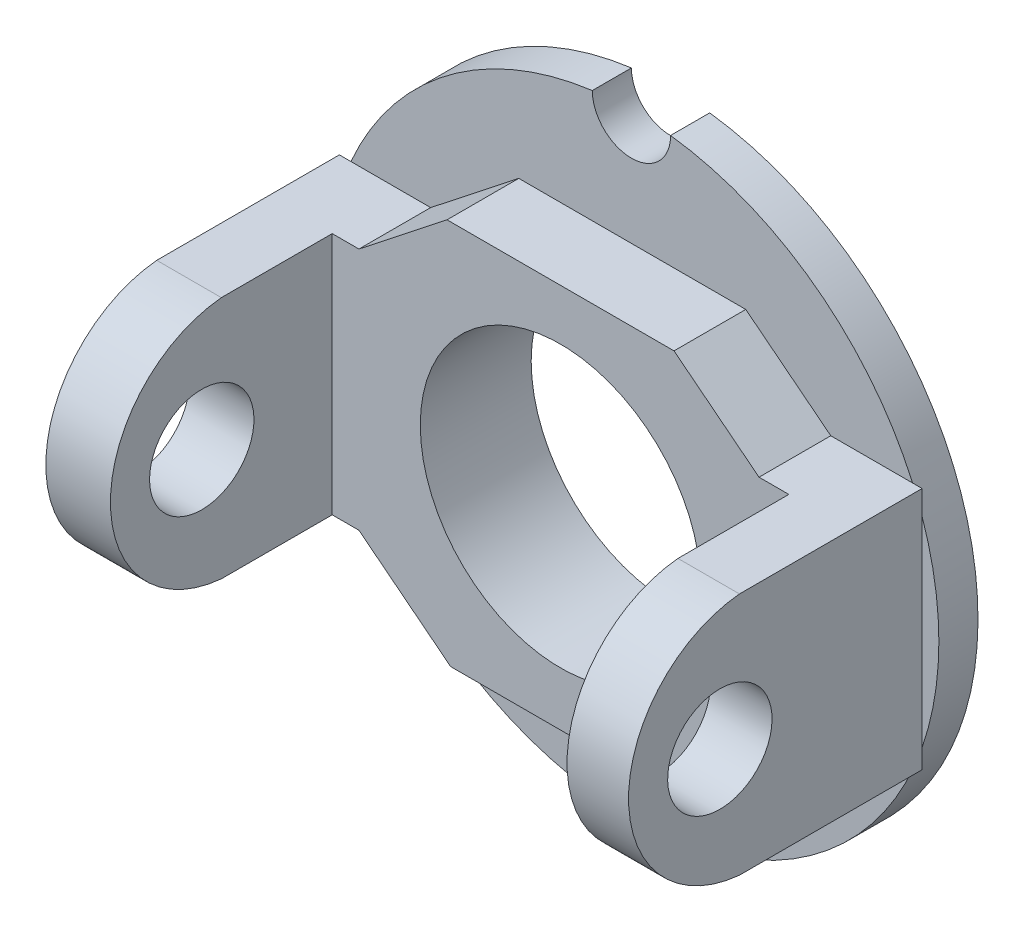
SolidWorks part; units mm, degrees
ref_plane "Plan de face" through (0, 0, 0) normal (0, 0, 1) x (1, 0, 0)
ref_plane "Plan de dessus" through (0, 0, 0) normal (0, 1, 0) x (1, 0, 0)
ref_plane "Plan de droite" through (0, 0, 0) normal (1, 0, 0) x (0, 0, -1)
sketch "Sketch1" plane through (0, 0, 0) normal (0, 0, 1) x (1, 0, 0)
  circle A0 centre (0, 0) radius 10.75
  arc A1 (2.9335, 23.3162) -> (-3.0665, 23.2991) centre (0, 0) cw
  arc A3 (-3.0665, 23.2991) -> (2.9335, 23.3162) centre (-0.0665, 23.3076) ccw
  point P5 (0.0671, -23.4999)
  point P6 (-0.0665, 23.5001)
  dimension "D1" = 21.5
  dimension "D3" = 23.5
  dimension "D4" = 3
  dimension "D2" = 47
  dimension "D5" = 6
extrude "Boss-Extrude1" add sketch "Sketch1" along normal blind 3
sketch "Sketch2" plane through (0, 0, 3) normal (0, 0, 1) x (1, 0, 0)
  line L0 (0, 0) -> (0, 14.6508) construction
  line L1 (-8.7, 14.6508) -> (8.7, 14.6508)
  line L7 (-15.4527, -9.335) -> (-15.4527, 9.335)
  line L8 (-15.4527, 9.335) -> (-8.7, 14.6508)
  line L9 (8.7, 14.6508) -> (15.2147, 9.5224)
  line L10 (15.2147, 9.5224) -> (15.2147, -9.1476)
  line L14 (-8.4225, -14.8692) -> (7.9465, -14.8692)
  line L15 (-8.4225, -14.8692) -> (-15.4527, -9.335)
  line L16 (15.2147, -9.1476) -> (7.9465, -14.8692)
  line L18 (15.2147, 9.5224) -> (22.2147, 9.5224)
  line L19 (15.2147, 9.5224) -> (15.2147, -9.1476)
  line L20 (15.2147, -9.1476) -> (22.2147, -9.1476)
  line L21 (22.2147, 9.5224) -> (22.2147, -9.1476)
  line L22 (-15.4527, 9.335) -> (-22.4527, 9.335)
  line L23 (-15.4527, 9.335) -> (-15.4527, -9.335)
  line L24 (-15.4527, -9.335) -> (-22.4527, -9.335)
  line L25 (-22.4527, 9.335) -> (-22.4527, -9.335)
  circle A0 centre (0, 0) radius 10.75
  point P12 (-15.4527, 0)
  point P13 (0, 14.6508)
  dimension "D1" = 18.67
  dimension "D2" = 141.79
  dimension "D3" = 17.4
  dimension "D4" = 141.79
  dimension "D5" = 18.67
  dimension "D6" = 29.52
  dimension "D7" = 141.79
  dimension "D8" = 141.79
  dimension "D9" = 7
  dimension "D10" = 7
extrude "Boss-Extrude2" add sketch "Sketch2" along normal blind 5.5
sketch "Sketch3" plane through (0, 0, 8.5) normal (0, 0, 1) x (1, 0, 0)
  line L0 (-15.4527, -9.335) -> (-22.4527, -9.335) construction
  line L1 (-22.4527, 9.335) -> (-17.5, 9.335)
  line L2 (-22.4527, 9.335) -> (-22.4527, -9.335)
  line L3 (-22.4527, -9.335) -> (-17.5, -9.335)
  line L4 (-17.5, 9.335) -> (-17.5, -9.335)
  line L5 (15.2147, -9.1476) -> (22.2147, -9.1476) construction
  line L6 (22.2147, 9.5224) -> (17.5, 9.5224)
  line L7 (22.2147, 9.5224) -> (22.2147, -9.1476)
  line L8 (22.2147, -9.1476) -> (17.5, -9.1476)
  line L9 (17.5, 9.5224) -> (17.5, -9.1476)
  dimension "D1" = 35
  dimension "D2" = 17.5
extrude "Boss-Extrude3" add sketch "Sketch3" along normal blind 17
sketch "Sketch4" plane through (-22.4527, 0, 0) normal (-1, 0, 0) x (0, 0, 1)
  line L0 (25.5, 9.335) -> (17, 9.335) construction
  line L1 (25.5, 9.335) -> (3, 9.335) construction
  line L2 (25.5, -9.335) -> (17, -9.335) construction
  line L4 (25.5, -9.335) -> (3, -9.335) construction
  line L5 (17, 9.335) -> (17, 13.6336)
  line L6 (17, 13.6336) -> (31.0273, 13.6336)
  line L7 (31.0273, 13.6336) -> (31.0273, -15.4296)
  line L8 (31.0273, -15.4296) -> (17, -15.4296)
  line L9 (17, -15.4296) -> (17, -9.335)
  arc A0 (17, 9.335) -> (17, -9.335) centre (16.124, 0) cw
  dimension "D1" = 8.5
  dimension "D2" = 8.5
extrude "Cut-Extrude1" cut sketch "Sketch4" against normal blind 17
sketch "Sketch5" plane through (-22.4527, 0, 0) normal (-1, 0, 0) x (0, 0, 1)
  circle A0 centre (18.5, 0.0017) radius 4
  arc A1 (17, -9.335) -> (17, 9.335) centre (16.124, 0) ccw construction
  point P5 (25.5, 0)
  dimension "D2" = 8
  dimension "D1" = 7
extrude "Cut-Extrude2" cut sketch "Sketch5" against normal blind 17
sketch "Sketch6" plane through (22.2147, 0, 0) normal (1, 0, 0) x (0, 0, -1)
  line L0 (-25.5, -9.1476) -> (-17, -9.1476) construction
  line L1 (-25.5, -9.1476) -> (-3, -9.1476) construction
  line L2 (-17, -9.1476) -> (-17, 9.5224) construction
  line L3 (-25.5, 9.5224) -> (-3, 9.5224) construction
  line L4 (-17, 9.5224) -> (-25.5, 9.5224) construction
  line L5 (-17, 9.5224) -> (-17, 12.0176)
  line L6 (-17, 12.0176) -> (-28.3232, 12.0176)
  line L7 (-28.3232, 12.0176) -> (-28.3232, -10.5543)
  line L8 (-28.3232, -10.5543) -> (-17, -10.5543)
  line L9 (-17, -10.5543) -> (-17, -9.1476)
  arc A0 (-17, -9.1476) -> (-17, 9.5224) centre (-16.124, 0.1874) cw
  dimension "D1" = 8.5
extrude "Cut-Extrude3" cut sketch "Sketch6" against normal blind 17
sketch "Sketch7" plane through (22.2147, 0, 0) normal (1, 0, 0) x (0, 0, -1)
  circle A0 centre (-18.5032, -0.0237) radius 4
  arc A1 (-17, 9.5224) -> (-17, -9.1476) centre (-16.124, 0.1874) ccw construction
  point P5 (-25.5, 0.1874)
  dimension "D2" = 8
  dimension "D1" = 7
extrude "Cut-Extrude4" cut sketch "Sketch7" against normal blind 17
